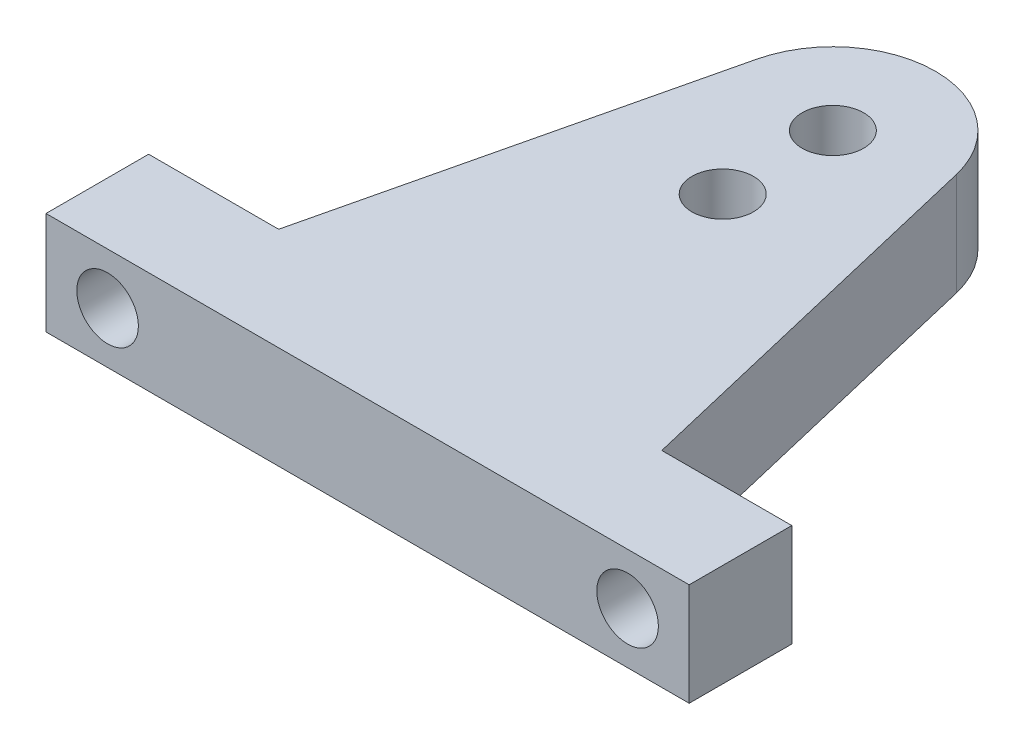
SolidWorks part; units mm, degrees
ref_plane "Alzado" through (0, 0, 0) normal (0, 0, 1) x (1, 0, 0)
ref_plane "Planta" through (0, 0, 0) normal (0, 1, 0) x (1, 0, 0)
ref_plane "Vista lateral" through (0, 0, 0) normal (1, 0, 0) x (0, 0, -1)
sketch "Croquis1" plane through (0, 0, 0) normal (0, 1, 0) x (1, 0, 0)
  line L0 (47, 0) -> (-47, 0)
  line L1 (-47, 0) -> (-47, 15)
  line L2 (-47, 15) -> (-28, 15)
  line L3 (47, 0) -> (47, 15)
  line L4 (47, 15) -> (28, 15)
  line L5 (-14.5943, 71.4649) -> (-28, 15)
  line L6 (14.5943, 71.4649) -> (28, 15)
  arc A0 (14.5943, 71.4649) -> (-14.5943, 71.4649) centre (0, 68) ccw
  dimension "D8" = 15
  dimension "D1" = 47
  dimension "D2" = 47
  dimension "D3" = 28
  dimension "D4" = 28
  dimension "D5" = 15
  dimension "D6" = 15
  dimension "D7" = 68
extrude "Saliente-Extruir1" add sketch "Croquis1" along normal blind 15
sketch "Croquis2" plane through (0, 0, 0) normal (0, 0, 1) x (1, 0, 0)
  line L0 (-47, 0) -> (47, 0) construction
  circle A0 centre (-38, 7.5) radius 4.5
  circle A1 centre (38, 7.5) radius 4.5
  dimension "D1" = 9
  dimension "D2" = 9
  dimension "D3" = 38
  dimension "D5" = 7.5
  dimension "D6" = 7.5
  dimension "D4" = 38
extrude "Cortar-Extruir1" cut sketch "Croquis2" against normal up to next
sketch "Croquis3" plane through (0, 15, 0) normal (0, 1, 0) x (1, 0, 0)
  circle A0 centre (0, 68) radius 4.5
  circle A1 centre (0, 51.9) radius 4.5
  dimension "D1" = 9
  dimension "D2" = 9
  dimension "D3" = 16.1
extrude "Cortar-Extruir2" cut sketch "Croquis3" against normal up to next
